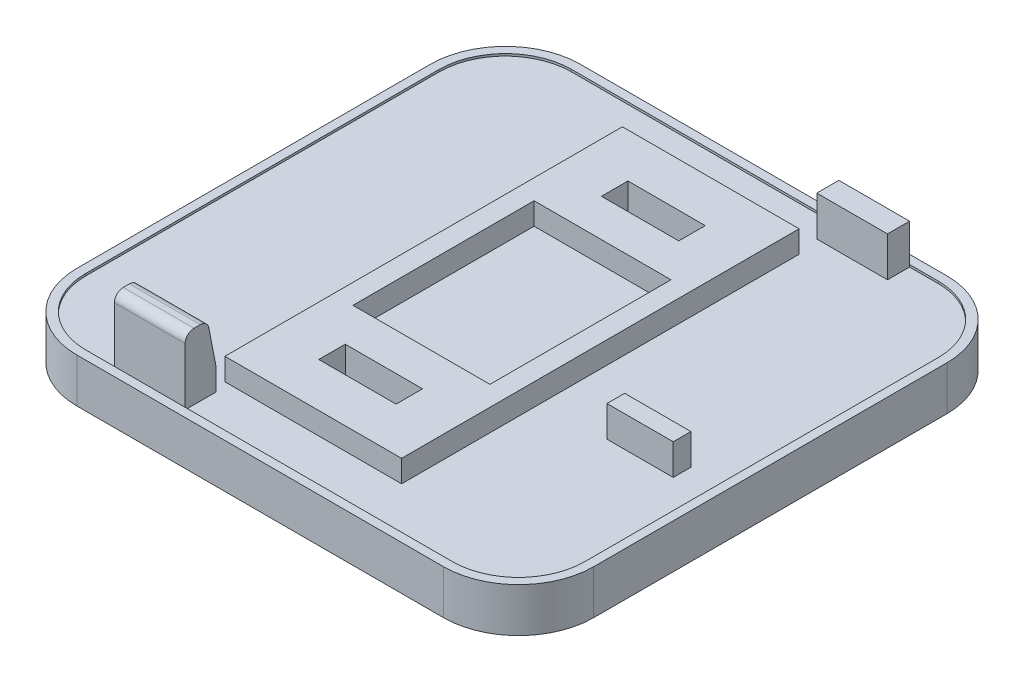
SolidWorks part; units mm, degrees
ref_plane "Plano frontal" through (0, 0, 0) normal (0, 0, 1) x (1, 0, 0)
ref_plane "Plano superior" through (0, 0, 0) normal (0, 1, 0) x (1, 0, 0)
ref_plane "Plano direito" through (0, 0, 0) normal (1, 0, 0) x (0, 0, -1)
sketch "Esboço1" plane through (0, 0, 0) normal (0, 1, 0) x (1, 0, 0)
  line L1 (-8.3, -11.4) -> (8.3, -11.4)
  line L2 (-11.7, -8) -> (-11.7, 8)
  line L3 (-8.3, 11.4) -> (8.3, 11.4)
  line L4 (11.7, -8) -> (11.7, 8)
  line L5 (-11.7, -11.4) -> (11.7, 11.4) construction
  line L6 (-11.7, 11.4) -> (11.7, -11.4) construction
  arc A0 (-8.3, -11.4) -> (-11.7, -8) centre (-8.3, -8) cw
  arc A1 (8.3, -11.4) -> (11.7, -8) centre (8.3, -8) ccw
  arc A2 (8.3, 11.4) -> (11.7, 8) centre (8.3, 8) cw
  arc A3 (-11.7, 8) -> (-8.3, 11.4) centre (-8.3, 8) cw
  point P0 (0, 0)
  dimension "D3" = 3.4
  dimension "D1" = 23.4
  dimension "D2" = 22.8
extrude "Ressalto-extrusão1" add sketch "Esboço1" along normal blind 2
sketch "Esboço2" plane through (0, 2, 0) normal (0, 1, 0) x (1, 0, 0)
  line L0 (8.3, 11.4) -> (-8.3, 11.4) construction
  line L1 (-8.3, -11) -> (8.3, -11)
  line L2 (-11.3, -8) -> (-11.3, 8)
  line L3 (-8.3, 11) -> (8.3, 11)
  line L4 (11.3, -8) -> (11.3, 8)
  line L5 (-11.3, -11) -> (11.3, 11) construction
  line L6 (-11.3, 11) -> (11.3, -11) construction
  line L7 (-11.7, 8) -> (-11.7, -8) construction
  arc A0 (-8.3, -11) -> (-11.3, -8) centre (-8.3, -8) cw
  arc A1 (8.3, -11) -> (11.3, -8) centre (8.3, -8) ccw
  arc A2 (8.3, 11) -> (11.3, 8) centre (8.3, 8) cw
  arc A3 (-11.3, 8) -> (-8.3, 11) centre (-8.3, 8) cw
  point P0 (0, 0)
  dimension "D3" = 3
  dimension "D1" = 0.4
  dimension "D2" = 0.4
extrude "Corte-extrusão1" cut sketch "Esboço2" against normal blind 0.1
sketch "Esboço3" plane through (0, 1.9, 0) normal (0, 1, 0) x (1, 0, 0)
  line L1 (-4, -9) -> (4, -9)
  line L2 (-4, -9) -> (-4, 9)
  line L3 (-4, 9) -> (4, 9)
  line L4 (4, -9) -> (4, 9)
  line L5 (-4, -9) -> (4, 9) construction
  line L6 (-4, 9) -> (4, -9) construction
  line L7 (-3.1, -4.1) -> (3.1, -4.1)
  line L8 (-3.1, -4.1) -> (-3.1, 4.1)
  line L9 (-3.1, 4.1) -> (3.1, 4.1)
  line L10 (3.1, -4.1) -> (3.1, 4.1)
  line L11 (-3.1, -4.1) -> (3.1, 4.1) construction
  line L12 (-3.1, 4.1) -> (3.1, -4.1) construction
  point P0 (0, 0)
  point P6 (0, 0)
  dimension "D1" = 18
  dimension "D2" = 8
  dimension "D3" = 6.2
  dimension "D4" = 8.2
extrude "Ressalto-extrusão2" add sketch "Esboço3" along normal blind 1
sketch "Esboço4" plane through (0, 1.9, 0) normal (0, 1, 0) x (1, 0, 0)
  line L0 (8.3, 11) -> (-8.3, 11) construction
  line L1 (7, 11) -> (3.8, 11)
  line L2 (7, 11) -> (7, 10)
  line L3 (7, 10) -> (3.8, 10)
  line L4 (3.8, 11) -> (3.8, 10)
  line L5 (4, -9) -> (4, 9) construction
  dimension "D1" = 3.2
  dimension "D2" = 3
  dimension "D3" = 1
extrude "Ressalto-extrusão3" add sketch "Esboço4" along normal blind 1.8
sketch "Esboço5" plane through (0, 1.9, 0) normal (0, 1, 0) x (1, 0, 0)
  line L0 (-8.3, -11) -> (8.3, -11) construction
  line L1 (-3.8, -11) -> (-7, -11)
  line L2 (-3.8, -11) -> (-3.8, -9.6)
  line L3 (-3.8, -9.6) -> (-7, -9.6)
  line L4 (-7, -11) -> (-7, -9.6)
  line L5 (-4, 9) -> (-4, -9) construction
  dimension "D1" = 3.2
  dimension "D2" = 3
  dimension "D3" = 1.4
extrude "Ressalto-extrusão4" add sketch "Esboço5" along normal blind 3
chamfer "Chanfro1" distance 2 angle 11 1 edges at (-5.4, 4.9, 9.6)
fillet "Filete1" radius 0.4 2 edges at (-5.4, 4.9, 11) (-5.4, 4.9, 9.9888)
sketch "Esboço6" plane through (0, 1.9, 0) normal (0, 1, 0) x (1, 0, 0)
  line L0 (-8.3, -11.4) -> (8.3, -11.4) construction
  line L1 (6.9, -1.8) -> (9.9, -1.8)
  line L2 (6.9, -1.8) -> (6.9, -2.6)
  line L3 (6.9, -2.6) -> (9.9, -2.6)
  line L4 (9.9, -1.8) -> (9.9, -2.6)
  line L5 (11.7, -8) -> (11.7, 8) construction
  dimension "D1" = 3
  dimension "D2" = 0.8
  dimension "D3" = 8.8
  dimension "D4" = 1.8
extrude "Ressalto-extrusão5" add sketch "Esboço6" along normal blind 1.4
sketch "Esboço7" plane through (0, 2.9, 0) normal (0, 1, 0) x (1, 0, 0)
  line L1 (-1.75, 5.8) -> (1.75, 5.8)
  line L2 (-1.75, 5.8) -> (-1.75, 7)
  line L3 (-1.75, 7) -> (1.75, 7)
  line L4 (1.75, 5.8) -> (1.75, 7)
  line L5 (-1.75, 5.8) -> (1.75, 7) construction
  line L6 (-1.75, 7) -> (1.75, 5.8) construction
  line L7 (-1.75, -7) -> (1.75, -7)
  line L8 (-1.75, -7) -> (-1.75, -5.8)
  line L9 (-1.75, -5.8) -> (1.75, -5.8)
  line L10 (1.75, -7) -> (1.75, -5.8)
  line L11 (-1.75, -7) -> (1.75, -5.8) construction
  line L12 (-1.75, -5.8) -> (1.75, -7) construction
  point P0 (0, 6.4)
  point P5 (0, -6.4)
  dimension "D1" = 3.5
  dimension "D2" = 3.5
  dimension "D3" = 0
  dimension "D4" = 0
  dimension "D5" = 1.2
  dimension "D6" = 1.2
  dimension "D7" = 5.8
  dimension "D8" = 5.8
extrude "Corte-extrusão2" cut sketch "Esboço7" against normal blind 5
